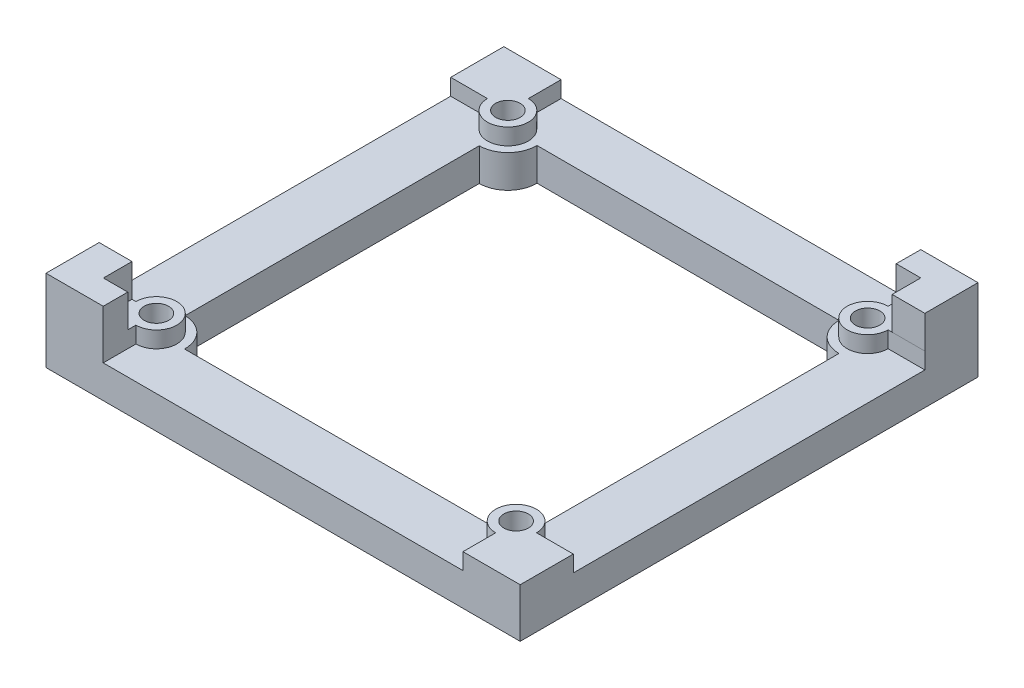
SolidWorks part; units mm, degrees
ref_plane "前视基准面" through (0, 0, 0) normal (0, 0, 1) x (1, 0, 0)
ref_plane "上视基准面" through (0, 0, 0) normal (0, 1, 0) x (1, 0, 0)
ref_plane "右视基准面" through (0, 0, 0) normal (1, 0, 0) x (0, 0, -1)
sketch "草图1" plane through (0, 0, 0) normal (0, 0, 1) x (1, 0, 0)
  line L2 (29, 0) -> (-29, 0)
  line L3 (29, 0) -> (29, -4)
  line L4 (29, -4) -> (-29, -4)
  line L5 (-29, 0) -> (-29, -4)
  line L6 (25, 1.64) -> (25, 0) construction
  line L7 (-25, 1.64) -> (-25, 0) construction
  line L8 (-118, -4) -> (29, -4) construction
  dimension "D1" = 4
  dimension "D2" = 4
extrude "凸台-拉伸1" add sketch "草图1" against normal blind 53 and the other way blind 3
sketch "草图2" plane through (0, 0, 0) normal (0, 1, 0) x (1, 0, 0)
  circle A0 centre (-22, 46.5) radius 1.5
  circle A1 centre (22, 46.5) radius 1.5
  circle A2 centre (22, 3.5) radius 1.5
  circle A3 centre (-22, 3.5) radius 1.5
extrude "切除-拉伸1" cut sketch "草图2" against normal blind 53
sketch "草图3" plane through (0, 0, 0) normal (0, 1, 0) x (1, 0, 0)
  circle A0 centre (-22, 46.5) radius 1.5
  circle A1 centre (-22, 46.5) radius 2.5
  circle A2 centre (22, 46.5) radius 1.5
  circle A3 centre (22, 46.5) radius 2.5
  circle A4 centre (22, 3.5) radius 2.5
  circle A5 centre (-22, 3.5) radius 1.5
  circle A6 centre (-22, 3.5) radius 2.5
  circle A7 centre (22, 3.5) radius 1.5
  dimension "D1" = 5
  dimension "D2" = 5
  dimension "D3" = 3
  dimension "D4" = 5
  dimension "D5" = 3
  dimension "D6" = 5
  dimension "D7" = 3
  dimension "D8" = 3
extrude "凸台-拉伸2" add sketch "草图3" along normal blind 2
sketch "草图4" plane through (0, 0, 0) normal (0, 1, 0) x (1, 0, 0)
  line L0 (-18.5, 46.56) -> (18.5, 46.5)
  line L1 (22, 43) -> (22, 7)
  line L3 (18.5, 3.5) -> (-18.5, 3.44)
  line L4 (-22, 7.0005) -> (-22, 42.9995)
  arc A0 (-22, 42.9995) -> (-18.5, 46.56) centre (-22, 46.5) ccw
  arc A1 (18.5, 46.5) -> (22, 43) centre (22, 46.5) ccw
  arc A2 (22, 7) -> (18.5, 3.5) centre (22, 3.5) ccw
  arc A3 (-18.5, 3.44) -> (-22, 7.0005) centre (-22, 3.5) ccw
extrude "切除-拉伸2" cut sketch "草图4" against normal blind 9
sketch "草图5" plane through (0, 0, 0) normal (0, 1, 0) x (1, 0, 0)
  line L0 (-22, 49) -> (-22, 53)
  line L1 (29, 53) -> (-29, 53) construction
  line L2 (-22, 53) -> (-29, 53)
  line L3 (-29, 53) -> (-29, 46.5)
  line L4 (-29, -3) -> (-29, 53) construction
  line L5 (-29, 46.5) -> (-24.5, 46.5)
  line L6 (-24.5, 46.5) -> (-22, 49)
  line L7 (22, 49) -> (22, 53)
  line L8 (22, 53) -> (29, 53)
  line L9 (29, 53) -> (29, 46.5)
  line L10 (29, -3) -> (29, 53) construction
  line L11 (29, 46.5) -> (24.5, 46.5)
  line L12 (24.5, 46.5) -> (22, 49)
  line L13 (24.5, 3.5) -> (29, 3.5)
  line L14 (29, 3.5) -> (29, -3)
  line L15 (29, -3) -> (22, -3)
  line L16 (29, -3) -> (-29, -3) construction
  line L17 (22, -3) -> (22, 1)
  line L18 (22, 1) -> (24.5, 3.5)
  line L19 (-24.5, 3.5) -> (-29, 3.5)
  line L20 (-29, 3.5) -> (-29, -3)
  line L21 (-29, -3) -> (-22, -3)
  line L22 (-22, -3) -> (-22, 1)
  line L23 (-22, 1) -> (-24.5, 3.5)
  circle A0 centre (-22, 46.5) radius 2.5 construction
  circle A1 centre (22, 46.5) radius 2.5 construction
  circle A2 centre (22, 3.5) radius 2.5 construction
  circle A3 centre (-22, 3.5) radius 2.5 construction
extrude "凸台-拉伸3" add sketch "草图5" along normal blind 2
sketch "草图6" plane through (0, 2, 0) normal (0, 1, 0) x (1, 0, 0)
  line L0 (-24.98, 3.5) -> (-24.98, 0)
  line L1 (-24.5, 3.5) -> (-29, 3.5) construction
  line L2 (-24.98, 0) -> (-22, 0)
  line L3 (-22, -3) -> (-22, 1) construction
  line L4 (-22, 0) -> (-22, -3)
  line L5 (-22, -3) -> (-29, -3)
  line L6 (-29, -3) -> (-29, 3.5)
  line L7 (-29, 3.5) -> (-24.98, 3.5)
  line L8 (20.1949, 50) -> (31.4917, 50) construction
  line L9 (25, 50) -> (-25, 50) construction
  line L10 (25, 45.4397) -> (25, 52.2045) construction
  line L11 (25, 28.2168) -> (25, 50) construction
  line L12 (21.9856, 50) -> (25, 50)
  line L13 (25, 50) -> (25, 46.5008)
  line L14 (25, 46.5008) -> (29, 46.5)
  line L15 (29, 46.5) -> (29, 53)
  line L16 (29, 53) -> (22, 53)
  line L17 (22, 53) -> (21.9856, 50)
extrude "凸台-拉伸4" add sketch "草图6" along normal blind 4
